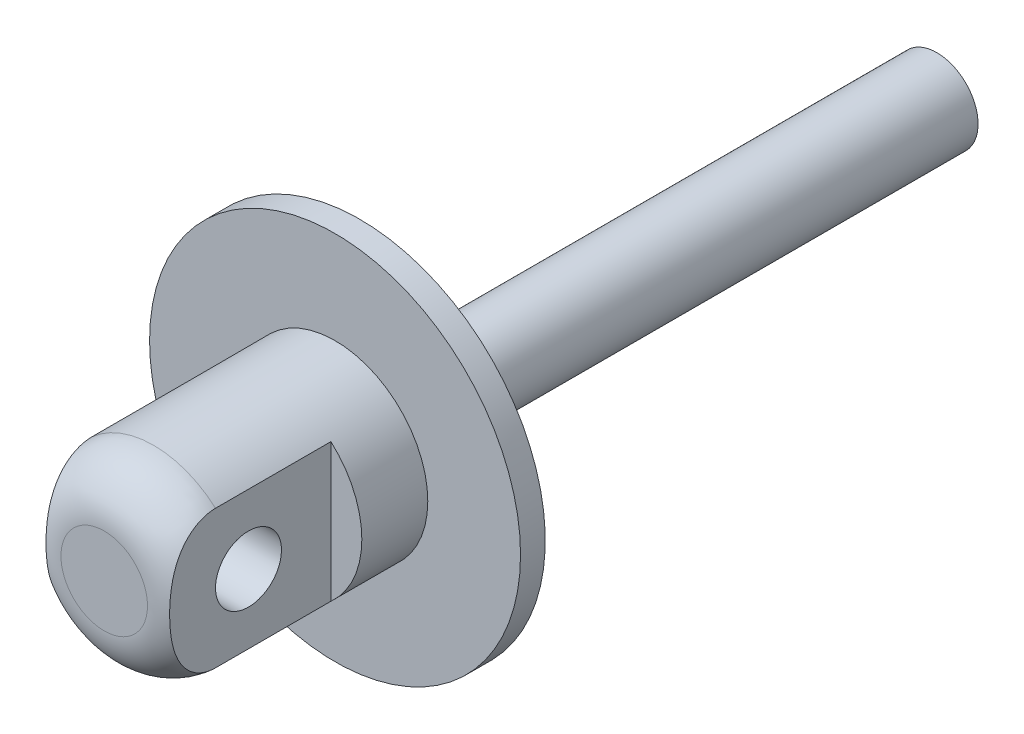
SolidWorks part; units mm, degrees
ref_plane "Plan de face" through (0, 0, 0) normal (0, 0, 1) x (1, 0, 0)
ref_plane "Plan de dessus" through (0, 0, 0) normal (0, 1, 0) x (1, 0, 0)
ref_plane "Plan de droite" through (0, 0, 0) normal (1, 0, 0) x (0, 0, -1)
sketch "Esquisse1" plane through (0, 0, 0) normal (0, 0, 1) x (1, 0, 0)
  circle A0 centre (0, 0) radius 22.5
  dimension "D1" = 45
extrude "Boss.-Extru.1" add sketch "Esquisse1" along normal blind 101
sketch "Esquisse2" plane through (0, 0, 0) normal (0, 0, -1) x (-1, 0, 0)
  circle A0 centre (0, 0) radius 22.5
  circle A1 centre (0, 0) radius 5
  dimension "D1" = 10
extrude "Enlèv. mat.-Extru.1" cut sketch "Esquisse2" against normal blind 70
sketch "Esquisse3" plane through (0, 0, 101) normal (0, 0, 1) x (1, 0, 0)
  circle A0 centre (0, 0) radius 22.5
  circle A1 centre (0, 0) radius 11.25
  dimension "D1" = 22.5
extrude "Enlèv. mat.-Extru.2" cut sketch "Esquisse3" against normal blind 28
fillet "Congé1" radius 6 1 edges at (11.25, 0, 101)
sketch "Esquisse6" plane through (0, 0, 101) normal (0, 0, 1) x (1, 0, 0)
  line L0 (0, 14.9126) -> (0, -9.7655) construction
  line L1 (7.5, 11.5282) -> (14.4099, 11.5282)
  line L2 (-7.5, -11.5282) -> (-14.4099, -11.5282)
  line L3 (-7.5, -11.5282) -> (-7.5, 11.5282)
  line L4 (-7.5, 11.5282) -> (-14.4099, 11.5282)
  line L5 (-14.4099, -11.5282) -> (-14.4099, 11.5282)
  line L6 (-7.5, -11.5282) -> (-14.4099, 11.5282) construction
  line L7 (-7.5, 11.5282) -> (-14.4099, -11.5282) construction
  line L8 (14.4099, -11.5282) -> (14.4099, 11.5282)
  line L9 (7.5, -11.5282) -> (14.4099, -11.5282)
  line L10 (7.5, -11.5282) -> (7.5, 11.5282)
  line L11 (7.5, 11.5282) -> (14.4099, -11.5282) construction
  line L12 (7.5, -11.5282) -> (14.4099, 11.5282) construction
  point P3 (-10.9549, 0)
  point P12 (10.9549, 0)
  dimension "D1" = 15
extrude "Enlèv. mat.-Extru.3" cut sketch "Esquisse6" against normal blind 20
sketch "Esquisse7" plane through (7.5, 0, 0) normal (1, 0, 0) x (0, 0, -1)
  line L0 (-81, 8.3853) -> (-81, -8.3853) construction
  circle A0 centre (-91, 0) radius 4
  dimension "D1" = 8
  dimension "D2" = 10
extrude "Enlèv. mat.-Extru.4" cut sketch "Esquisse7" against normal through all
